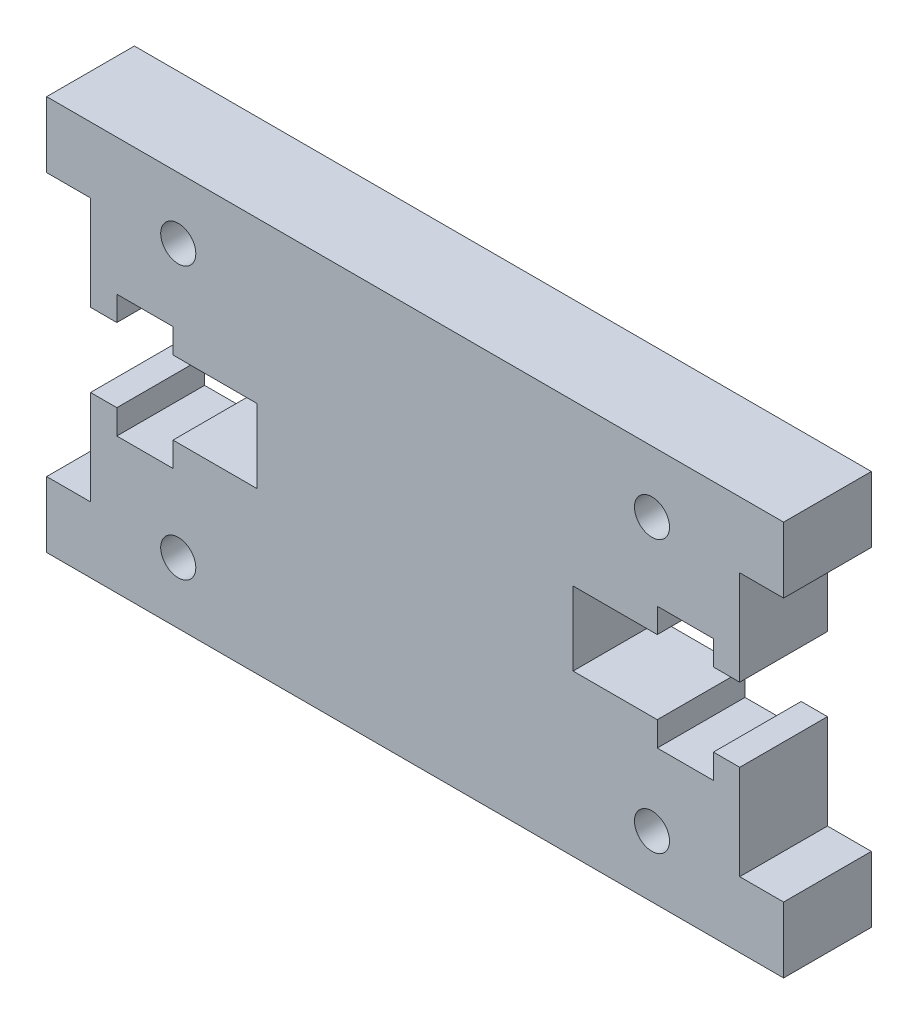
SolidWorks part; units mm, degrees
ref_plane "Plan de face" through (0, 0, 0) normal (0, 0, 1) x (1, 0, 0)
ref_plane "Plan de dessus" through (0, 0, 0) normal (0, 1, 0) x (1, 0, 0)
ref_plane "Plan de droite" through (0, 0, 0) normal (1, 0, 0) x (0, 0, -1)
sketch "Esquisse1" plane through (0, 0, 0) normal (0, 0, 1) x (1, 0, 0)
  line L0 (-21, -0.1216) -> (-21, -8.3527) construction
  line L1 (-4, 14.75) -> (-4, 7.75)
  line L2 (-42, 13.35) -> (-30, 13.35)
  line L4 (0, 0) -> (-42, 0)
  line L5 (0, 0) -> (0, 22.5)
  line L6 (0, 22.5) -> (-42, 22.5)
  line L7 (-42, 0) -> (-42, 22.5)
  line L17 (-42, 9.15) -> (-30, 9.15)
  line L18 (-6.7241, 11.25) -> (25.2759, 11.25) construction
  line L19 (-30, 13.35) -> (-30, 9.15)
  line L20 (-34.8, 14.75) -> (-38, 14.75)
  line L21 (-34.8, 14.75) -> (-34.8, 7.75)
  line L22 (-34.8, 7.75) -> (-38, 7.75)
  line L23 (-38, 14.75) -> (-38, 7.75)
  line L24 (-7.2, 14.75) -> (-7.2, 7.75)
  line L25 (-7.2, 14.75) -> (-4, 14.75)
  line L26 (-12, 13.35) -> (-12, 9.15)
  line L27 (0, 13.35) -> (-12, 13.35)
  line L28 (-7.2, 7.75) -> (-4, 7.75)
  line L29 (0, 9.15) -> (-12, 9.15)
  line L30 (0, 13.35) -> (0, 9.15)
  line L31 (-42, 13.35) -> (-42, 9.15)
  line L32 (0, 3.75) -> (-2.5, 3.75)
  line L33 (-42, 18.75) -> (-39.5, 18.75)
  line L34 (-42, 18.75) -> (-42, 3.75)
  line L35 (-42, 3.75) -> (-39.5, 3.75)
  line L36 (-39.5, 18.75) -> (-39.5, 3.75)
  line L37 (-2.5, 18.75) -> (-2.5, 3.75)
  line L38 (0, 18.75) -> (-2.5, 18.75)
  line L39 (0, 18.75) -> (0, 3.75)
  circle A6 centre (-34.5, 19) radius 1
  circle A7 centre (-7.5, 19) radius 1
  circle A8 centre (-7.5, 3.5) radius 1
  circle A10 centre (-34.5, 3.5) radius 1
  point P11 (-39.5, 11.25)
  point P22 (0, 0)
  point P23 (0, 0)
  point P30 (-7.25, 20.5732)
  point P35 (-30, 11.25)
  point P36 (-38, 11.25)
  dimension "D7" = 13.5
  dimension "D8" = 3.2
  dimension "D9" = 4
  dimension "D10" = 2
  dimension "D11" = 2
  dimension "D12" = 2.5
  dimension "D3" = 13.5
  dimension "D4" = 22.5
  dimension "D16" = 7.75
  dimension "D17" = 7.75
  dimension "D18" = 7.75
  dimension "D2" = 42
  dimension "D5" = 4.2
  dimension "D6" = 7
  dimension "D13" = 12
  dimension "D14" = 15
  dimension "D15" = 13.5
extrude "Boss.-Extru.1" add sketch "Esquisse1" along normal blind 5 contours L38 L5 L6 L7 L33 L36 L2 L23 L20 L21 L19 L17 L22 L35 L4 L32 L37 L29 L1 L28 L24 L26 L27 L25 A8 A7 A6 A10
